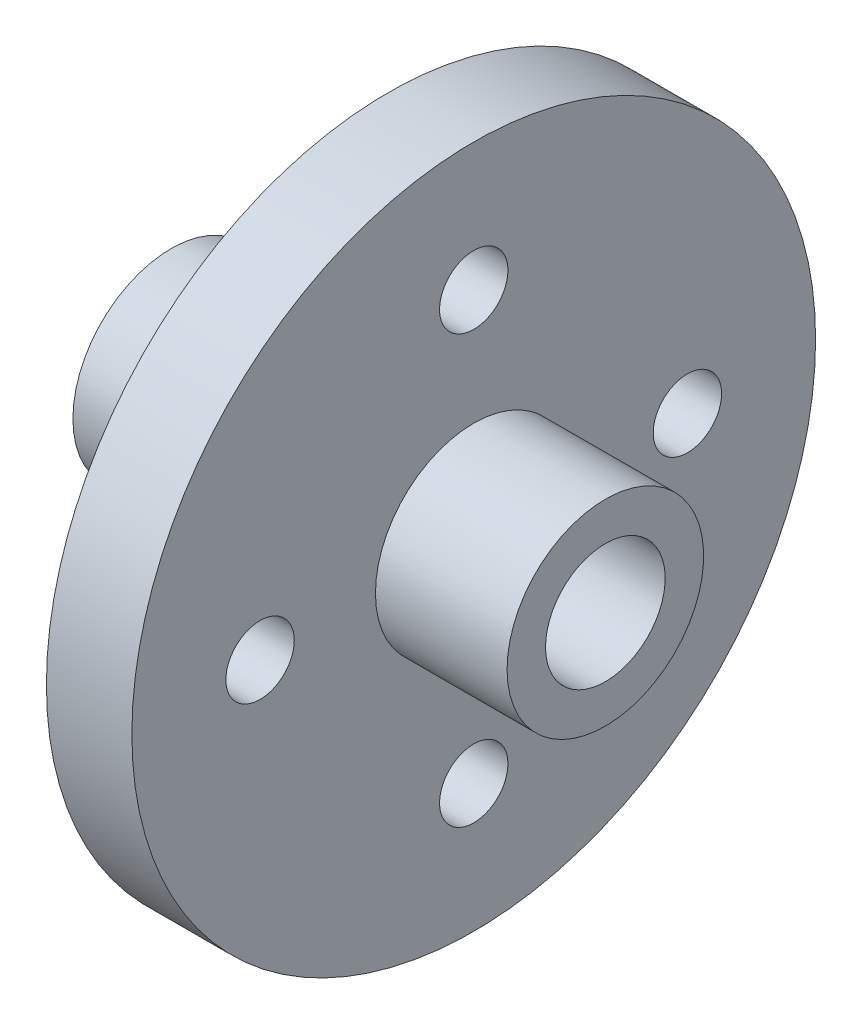
SolidWorks part; units mm, degrees
material "ABS"
ref_plane "Front Plane" through (0, 0, 0) normal (0, 0, 1) x (1, 0, 0)
ref_plane "Top Plane" through (0, 0, 0) normal (0, 1, 0) x (1, 0, 0)
ref_plane "Right Plane" through (0, 0, 0) normal (1, 0, 0) x (0, 0, -1)
sketch "Sketch1" plane through (0, 0, 0) normal (1, 0, 0) x (0, 0, -1)
  circle A0 centre (0, 0) radius 20
  circle A1 centre (0, 0) radius 3.5
  dimension "D1" = 40
  dimension "D2" = 7
extrude "Boss-Extrude1" add sketch "Sketch1" along normal blind 5
sketch "Sketch3" plane through (0, 0, 0) normal (-1, 0, 0) x (0, 0, 1)
  circle A0 centre (0, 0) radius 3.5 construction
  circle A1 centre (0, 0) radius 5.75
  circle A2 centre (0, 0) radius 3.5
  dimension "D1" = 11.5
extrude "Boss-Extrude2" add sketch "Sketch3" along normal blind 12.7 and the other way blind 12.7
hole_wizard "Ø4.0 (4) Diameter Hole1" positions "Sketch5" profile "Sketch4" hole size "Ø4.0" standard "ISO"
sketch "Sketch5" plane through (5, 0, 0) normal (1, 0, 0) x (0, 0, -1)
  point P0 (12.5, 0)
  point P2 (0, -12.5)
  point P4 (-12.5, 0)
  point P6 (0, 12.5)
  dimension "D1" = 25
  dimension "D2" = 25
  dimension "D3" = 12.5
  dimension "D4" = 12.5
sketch "Sketch4" plane through (5, 0, -12.5) normal (0, 1, 0) x (0, 0, -1)
  line L0 (0, 0) -> (0, 16.2017)
  line L1 (0, 16.2017) -> (2, 15)
  line L2 (2, 15) -> (2, 0)
  line L5 (2, 0) -> (0, 0)
  line L10 (0, 16.2017) -> (-2, 15) construction
  line L11 (0, -6.35) -> (0, 107.95) construction
  dimension "Hole Dia." = 4
  dimension "Hole Depth" = 15
  dimension "Drill Angle" = 118
